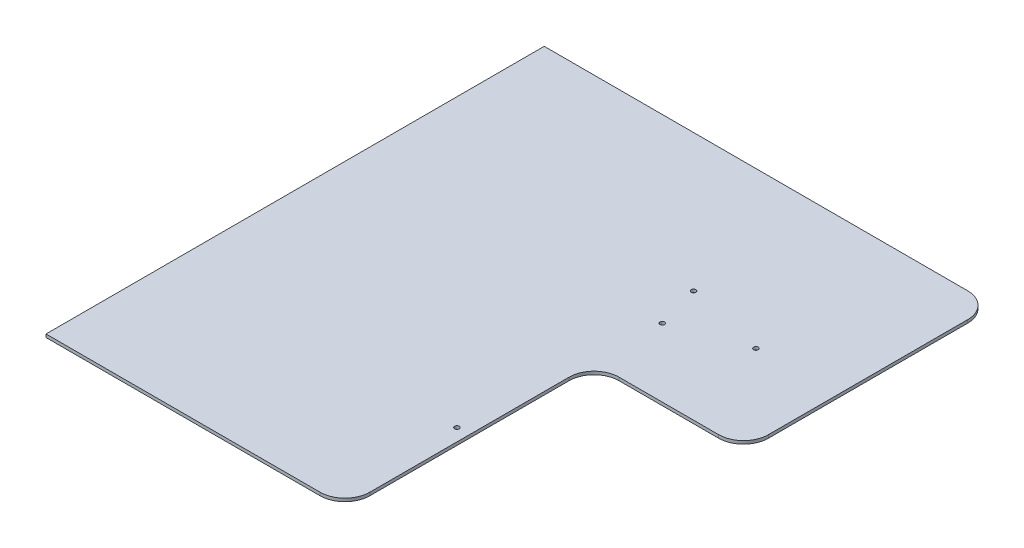
SolidWorks part; units mm, degrees
ref_plane "Front Plane" through (0, 0, 0) normal (0, 0, 1) x (1, 0, 0)
ref_plane "Top Plane" through (0, 0, 0) normal (0, 1, 0) x (1, 0, 0)
ref_plane "Right Plane" through (0, 0, 0) normal (1, 0, 0) x (0, 0, -1)
sketch "Sketch1" plane through (0, 0, 0) normal (0, 1, 0) x (1, 0, 0)
  line L1 (-152.4, -254) -> (152.4, -254)
  line L2 (-152.4, -254) -> (-152.4, 254)
  line L3 (-152.4, 254) -> (152.4, 254)
  line L4 (152.4, -254) -> (152.4, 254)
  line L5 (-152.4, -254) -> (152.4, 254) construction
  line L6 (-152.4, 254) -> (152.4, -254) construction
  point P0 (0, 0)
  dimension "D1" = 508
  dimension "D2" = 304.8
extrude "Boss-Extrude1" add sketch "Sketch1" along normal blind 3.175
sketch "Sketch2" plane through (0, 3.175, 0) normal (0, 1, 0) x (1, 0, 0)
  line L0 (152.4, -254) -> (152.4, 254) construction
  line L1 (139.7, 114.1276) -> (139.7, -127.1724) construction
  circle A0 centre (139.7, -127.1724) radius 2.3812
  circle A1 centre (139.7, 114.1276) radius 2.3813
  dimension "D2" = 4.7625
  dimension "D4" = 4.7625
  dimension "D1" = 12.7
  dimension "D3" = 241.3
sketch "Sketch4" plane through (152.4, 0, 0) normal (1, 0, 0) x (0, 0, -1)
  line L0 (0, 0) -> (0, 3.175)
  line L1 (0, 0) -> (254.0031, 0)
  line L2 (0, 3.175) -> (254.0031, 3.175)
  line L3 (254.0031, 0) -> (254.0031, 3.175)
  line L4 (-254, 3.175) -> (254, 3.175) construction
extrude "Boss-Extrude2" add sketch "Sketch4" along normal blind 152.4
fillet "Fillet1" radius 25.4 1 edges
fillet "Fillet2" radius 25.4 2 edges at (304.8, 1.5875, -254.0031) (304.8, 1.5875, 0)
extrude "Cut-Extrude3" cut sketch "Sketch2" against normal blind 152.4
fillet "Fillet3" radius 25.4 1 edges at (152.4, 1.5875, 254)
sketch "Sketch5" plane through (0, 3.175, 0) normal (0, 1, 0) x (1, 0, 0)
  circle A0 centre (152.4, 69.6776) radius 2.3813
  circle A1 centre (222.25, 95.0776) radius 2.3813
  circle A2 centre (139.7, 114.1276) radius 2.3813
  dimension "D5" = 4.7625
  dimension "D6" = 4.7625
  dimension "D1" = 44.45
  dimension "D2" = 12.7
  dimension "D3" = 82.55
  dimension "D4" = 19.05
extrude "Cut-Extrude4" cut sketch "Sketch5" against normal through all
